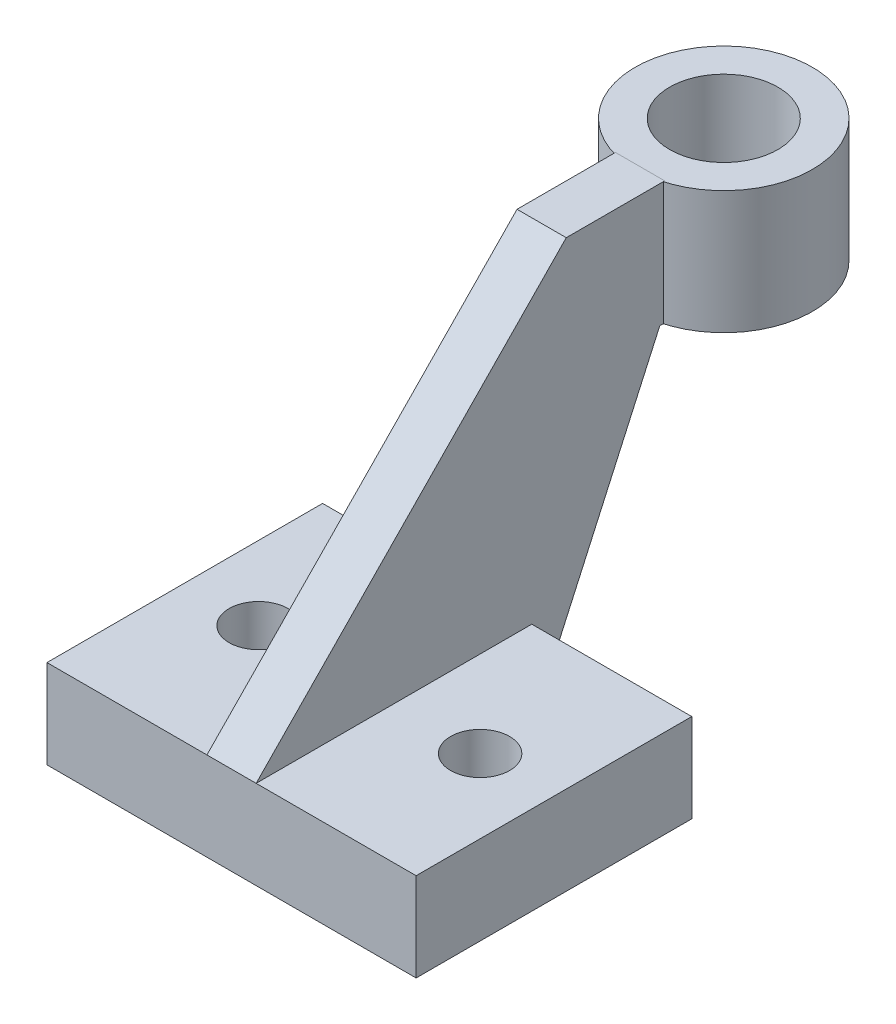
SolidWorks part; units mm, degrees
ref_plane "Front Plane" through (0, 0, 0) normal (0, 0, 1) x (1, 0, 0)
ref_plane "Top Plane" through (0, 0, 0) normal (0, 1, 0) x (1, 0, 0)
ref_plane "Right Plane" through (0, 0, 0) normal (1, 0, 0) x (0, 0, -1)
sketch "Sketch1" plane through (0, 0, 0) normal (1, 0, 0) x (0, 0, -1)
  line L0 (0, 0) -> (0, 30.5547) construction
  line L1 (-28, 18) -> (28, 18)
  line L2 (-28, 18) -> (-28, 0)
  line L3 (-28, 0) -> (28, 0)
  line L4 (28, 18) -> (28, 0)
  dimension "D1" = 56
  dimension "D2" = 18
extrude "Boss-Extrude1" add sketch "Sketch1" along normal mid plane 75
ref_plane "Plane1" through (0, 70, 0) normal (0, 1, 0) x (1, 0, 0)
sketch "Sketch3" plane through (0, 70, 0) normal (0, 1, 0) x (1, 0, 0)
  circle A0 centre (0, 72) radius 18
  circle A1 centre (0, 72) radius 11
  point P3 (0, 0)
  dimension "D1" = 36
  dimension "D2" = 22
  dimension "D3" = 72
extrude "Boss-Extrude2" add sketch "Sketch3" along normal mid plane 25 separate body
sketch "Sketch4" plane through (0, 0, 0) normal (1, 0, 0) x (0, 0, -1)
  line L0 (-28, 18) -> (35, 82.5)
  line L1 (35, 82.5) -> (55, 82.5)
  line L3 (54, 57.5) -> (28, 0)
  line L4 (28, 0) -> (28, 18)
  line L5 (28, 18) -> (-28, 18)
  line L6 (90, 82.5) -> (54, 82.5) construction
  line L7 (55, 82.5) -> (55, 57.5)
  line L8 (54, 57.5) -> (90, 57.5) construction
  line L9 (55, 57.5) -> (54, 57.5)
  dimension "D1" = 35
  dimension "D2" = 55
extrude "Boss-Extrude3" add sketch "Sketch4" along normal mid plane 10
hole_wizard "Hole1" positions "Sketch5" profile "Sketch6" legacy end condition up to next
sketch "Sketch5" plane through (0, 18, 0) normal (0, 1, 0) x (1, 0, 0)
  line L0 (-37.5, 28) -> (-37.5, -28) construction
  point P2 (-22.5, 0)
  point P9 (-22.5, 0)
  point P11 (-22.5, 0)
  point P12 (0, 0)
  point P13 (0, 0)
  dimension "D1" = 15
sketch "Sketch6" plane through (-22.5, 18, 0) normal (1, 0, 0) x (0, 0, 1)
  line L0 (0, 0) -> (0, 18.001)
  line L1 (0, 18.001) -> (6, 18.001)
  line L2 (6, 18.001) -> (6, 0)
  line L3 (6, 0) -> (0, 0)
  line L4 (0, 110) -> (0, -10) construction
  dimension "Diameter" = 12
  dimension "Depth" = 18.001
mirror "Mirror1" about plane through (0, 0, 0) normal (1, 0, 0) of "Hole1"
